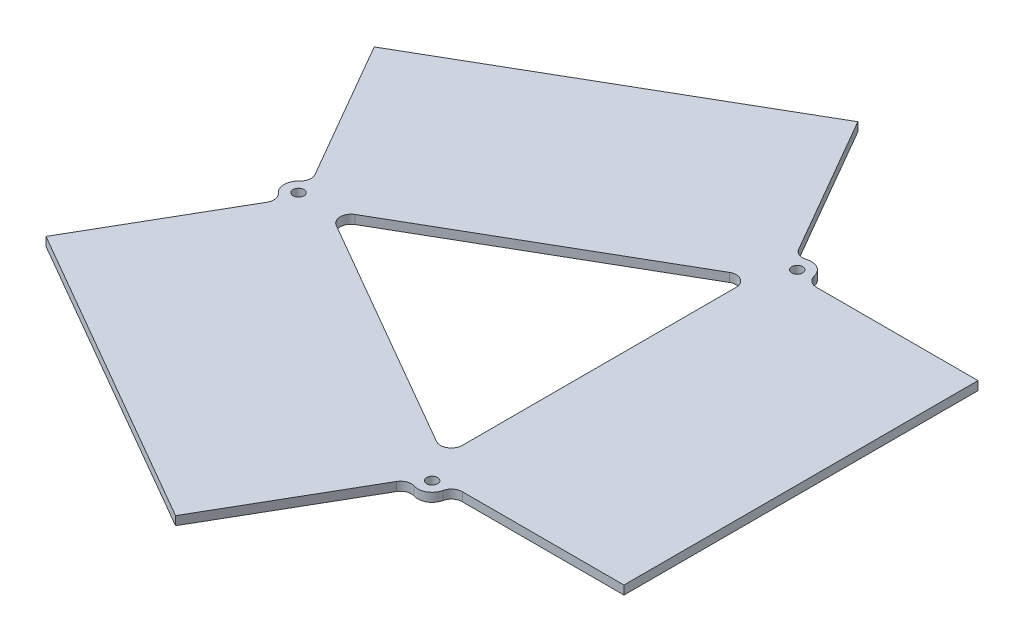
SolidWorks part; units mm, degrees
material "Acrylic (Medium-high impact)"
ref_plane "Front Plane" through (0, 0, 0) normal (0, 0, 1) x (1, 0, 0)
ref_plane "Top Plane" through (0, 0, 0) normal (0, 1, 0) x (1, 0, 0)
ref_plane "Right Plane" through (0, 0, 0) normal (1, 0, 0) x (0, 0, -1)
sketch "Sketch1" plane through (0, 0, 0) normal (0, 1, 0) x (1, 0, 0)
  line L0 (-80.9213, 31.2483) -> (-101.2337, 66.4304)
  line L1 (-103.9658, 67.1624) -> (-33.8177, 107.6624)
  line L2 (-33.8177, 107.6624) -> (-14.0109, 73.356)
  line L4 (-8.3973, 70.115) -> (31.2163, 70.115)
  line L5 (31.2163, 70.115) -> (31.2163, -10.885)
  line L6 (31.2163, -10.885) -> (-8.3973, -10.885)
  line L8 (-14.0109, -14.126) -> (-33.8177, -48.4324)
  line L9 (-33.8177, -48.4324) -> (-103.9658, -7.9324)
  line L10 (-103.9658, -7.9324) -> (-84.1589, 26.374)
  line L12 (-84.1589, 32.856) -> (-103.9658, 67.1624)
  line L13 (-101.2337, 66.4304) -> (-34.5498, 104.9304)
  line L14 (-34.5498, 104.9304) -> (-14.2374, 69.7483)
  line L15 (-11.4084, 68.115) -> (29.2163, 68.115)
  line L16 (29.2163, 68.115) -> (29.2163, -8.885)
  line L17 (29.2163, -8.885) -> (-11.4084, -8.885)
  line L18 (-14.2374, -10.5183) -> (-34.5498, -45.7004)
  line L19 (-34.5498, -45.7004) -> (-101.2337, -7.2004)
  line L20 (-101.2337, -7.2004) -> (-80.9213, 27.9817)
  line L21 (-83.7504, 29.615) -> (-76.6993, 29.615)
  line L22 (-11.4084, 71.3817) -> (-14.9339, 65.2753)
  line L23 (-11.4084, -12.1517) -> (-14.9339, -6.0453)
  line L24 (-76.6993, 29.615) -> (-14.9339, 65.2753)
  line L25 (-14.9339, -6.0453) -> (-14.9339, 65.2753)
  line L26 (-76.6993, 29.615) -> (-14.9339, -6.0453)
  circle A0 centre (-83.7504, 29.615) radius 1.25
  circle A1 centre (-11.4084, 71.3817) radius 1.25
  circle A2 centre (-11.4084, -12.1517) radius 1.25
  arc A3 (-80.9213, 27.9817) -> (-80.9213, 31.2483) centre (-83.7504, 29.615) ccw
  arc A4 (-8.3973, 70.115) -> (-14.0109, 73.356) centre (-11.4084, 71.3817) ccw
  arc A5 (-11.4084, -8.885) -> (-14.2374, -10.5183) centre (-11.4084, -12.1517) ccw
  arc A6 (-14.0109, -14.126) -> (-8.3973, -10.885) centre (-11.4084, -12.1517) ccw
  arc A7 (-84.1589, 32.856) -> (-84.1589, 26.374) centre (-83.7504, 29.615) ccw
  arc A8 (-14.2374, 69.7483) -> (-11.4084, 68.115) centre (-11.4084, 71.3817) ccw
extrude "Boss-Extrude1" add sketch "Sketch1" along normal blind 2
fillet "Fillet1" radius 2.5 9 edges at (-14.0109, 1, -73.356) (-8.3973, 1, -70.115) (-14.0109, 1, 14.126) (-8.3973, 1, 10.885) (-84.1589, 1, -26.374) (-84.1589, 1, -32.856) (-14.9339, 1, 6.0453) (-14.9339, 1, -65.2753) (-76.6993, 1, -29.615)
